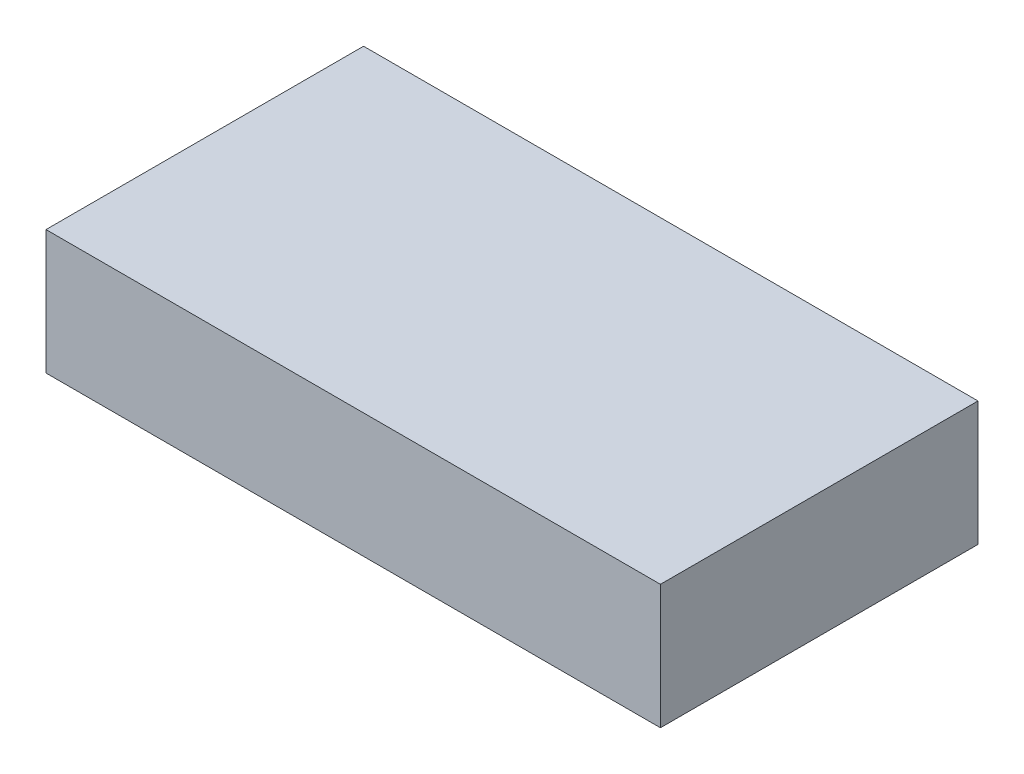
SolidWorks part; units mm, degrees
ref_plane "Front Plane" through (0, 0, 0) normal (0, 0, 1) x (1, 0, 0)
ref_plane "Top Plane" through (0, 0, 0) normal (0, 1, 0) x (1, 0, 0)
ref_plane "Right Plane" through (0, 0, 0) normal (1, 0, 0) x (0, 0, -1)
sketch "Sketch1" plane through (0, 0, 0) normal (0, 1, 0) x (1, 0, 0)
  line L1 (44.5, -23) -> (-44.5, -23)
  line L2 (44.5, -23) -> (44.5, 23)
  line L3 (44.5, 23) -> (-44.5, 23)
  line L4 (-44.5, -23) -> (-44.5, 23)
  line L5 (44.5, -23) -> (-44.5, 23) construction
  line L6 (44.5, 23) -> (-44.5, -23) construction
  point P0 (0, 0)
  dimension "D1" = 89
  dimension "D2" = 46
extrude "Boss-Extrude1" add sketch "Sketch1" along normal mid plane 18
